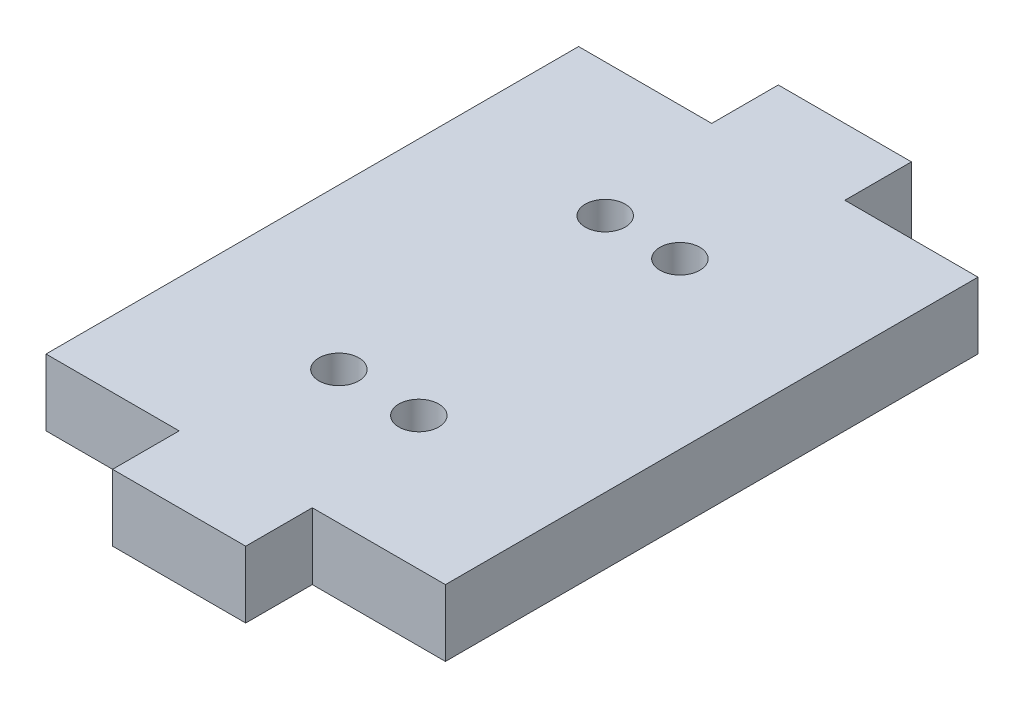
SolidWorks part; units mm, degrees
ref_plane "前视基准面" through (0, 0, 0) normal (0, 0, 1) x (1, 0, 0)
ref_plane "上视基准面" through (0, 0, 0) normal (0, 1, 0) x (1, 0, 0)
ref_plane "右视基准面" through (0, 0, 0) normal (1, 0, 0) x (0, 0, -1)
sketch "草图1" plane through (0, 0, 0) normal (0, 1, 0) x (1, 0, 0)
  line L0 (20, 40) -> (30, 40)
  line L1 (0, 0) -> (10, 0)
  line L2 (0, 0) -> (0, 40)
  line L3 (0, 40) -> (10, 40)
  line L4 (30, 0) -> (30, 40)
  line L5 (12, 37.3245) -> (12, 3.5096) construction
  line L6 (10, 40) -> (10, 45)
  line L7 (10, 45) -> (20, 45)
  line L8 (20, 40) -> (20, 45)
  line L9 (18, 35.7697) -> (18, 3.5096) construction
  line L10 (10, 0) -> (10, -5)
  line L11 (10, -5) -> (20, -5)
  line L12 (20, 0) -> (20, -5)
  line L13 (20, 0) -> (30, 0)
  line L15 (-9.5321, 30) -> (44.7531, 30) construction
  line L16 (39.9594, 10) -> (-12.9006, 10) construction
  circle A0 centre (12, 30) radius 1.5
  circle A1 centre (17.6105, 30) radius 1.5
  circle A2 centre (18, 10) radius 1.5
  circle A3 centre (12, 10) radius 1.5
  dimension "D1" = 30
  dimension "D2" = 40
  dimension "D3" = 10
  dimension "D4" = 5
  dimension "D5" = 10
  dimension "D6" = 5
  dimension "D7" = 10
  dimension "D8" = 10
  dimension "D9" = 6
  dimension "D10" = 12
  dimension "D11" = 10
  dimension "D12" = 10
extrude "凸台-拉伸1" add sketch "草图1" along normal blind 5
